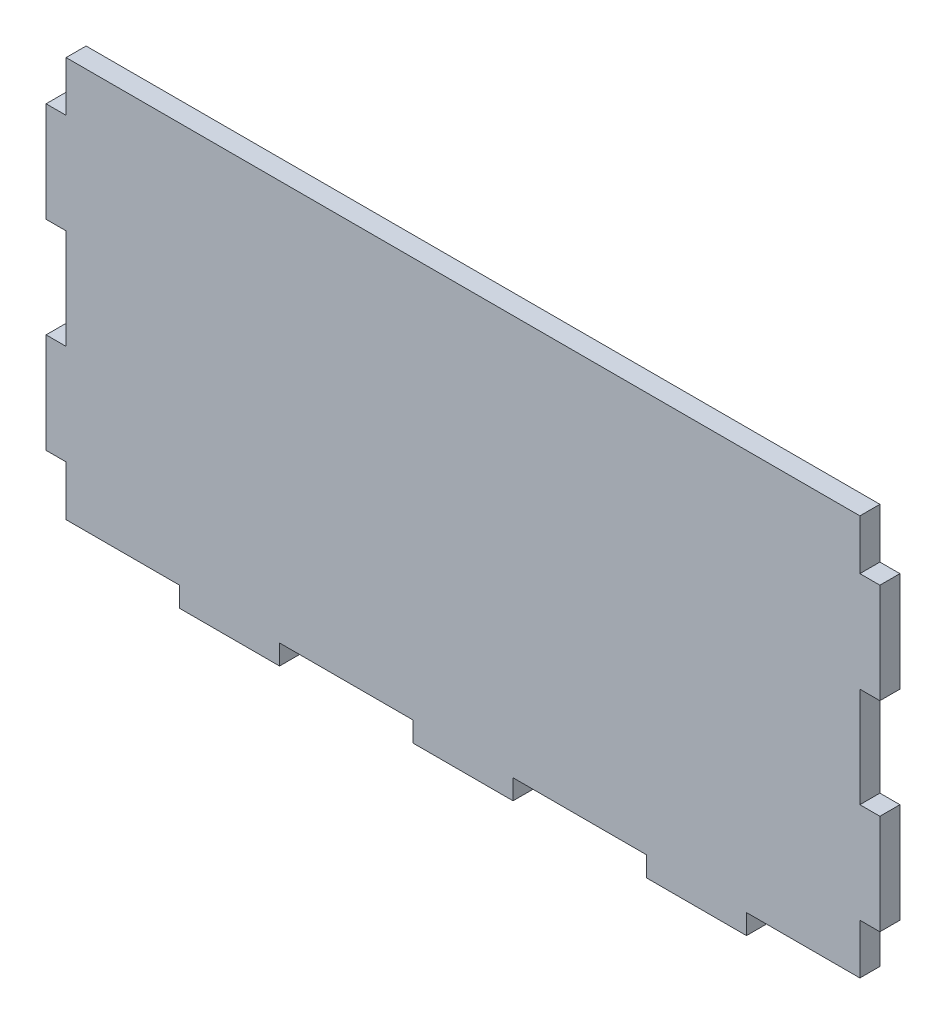
SolidWorks part; units mm, degrees
ref_plane "Спереди" through (0, 0, 0) normal (0, 0, 1) x (1, 0, 0)
ref_plane "Сверху" through (0, 0, 0) normal (0, 1, 0) x (1, 0, 0)
ref_plane "Справа" through (0, 0, 0) normal (1, 0, 0) x (0, 0, -1)
other "Configuration Table"
sketch "Эскиз1" plane through (0, 0, 0) normal (0, 0, 1) x (1, 0, 0)
  line L0 (-119, 0) -> (-119, -330.6864) construction
  line L1 (0, 0) -> (-238, 0)
  line L2 (0, 0) -> (0, -15)
  line L3 (0, -120) -> (-34, -120)
  line L4 (-238, 0) -> (-238, -15)
  line L5 (-34, -126) -> (-64, -126)
  line L7 (-134, -120) -> (-134, -126)
  line L8 (-134, -126) -> (-104, -126)
  line L9 (-104, -120) -> (-104, -126)
  line L11 (-204, -120) -> (-204, -126)
  line L12 (-204, -126) -> (-174, -126)
  line L13 (-174, -120) -> (-174, -126)
  line L14 (-64, -120) -> (-64, -126)
  line L16 (-34, -120) -> (-34, -126)
  line L17 (-204, -120) -> (-238, -120)
  line L18 (-64, -120) -> (-104, -120)
  line L19 (-134, -120) -> (-174, -120)
  line L20 (-238, -45) -> (-238, -75)
  line L21 (-238, -105) -> (-244, -105)
  line L23 (-238, -75) -> (-244, -75)
  line L24 (-244, -105) -> (-244, -75)
  line L25 (-238, -45) -> (-244, -45)
  line L27 (-238, -15) -> (-244, -15)
  line L28 (-244, -45) -> (-244, -15)
  line L29 (-238, -105) -> (-238, -120)
  line L30 (0, -105) -> (6, -105)
  line L31 (6, -105) -> (6, -75)
  line L32 (0, -75) -> (6, -75)
  line L33 (0, -45) -> (6, -45)
  line L34 (0, -15) -> (6, -15)
  line L35 (6, -45) -> (6, -15)
  line L36 (0, -45) -> (0, -75)
  line L37 (0, -105) -> (0, -120)
  dimension "D1" = 238
  dimension "D2" = 120
  dimension "D3" = 30
  dimension "D4" = 6
  dimension "D5" = 40
  dimension "D6" = 30
  dimension "D7" = 15
  dimension "D8" = 6
  dimension "D9" = 30
extrude "Бобышка-Вытянуть1" add sketch "Эскиз1" along normal blind 6
